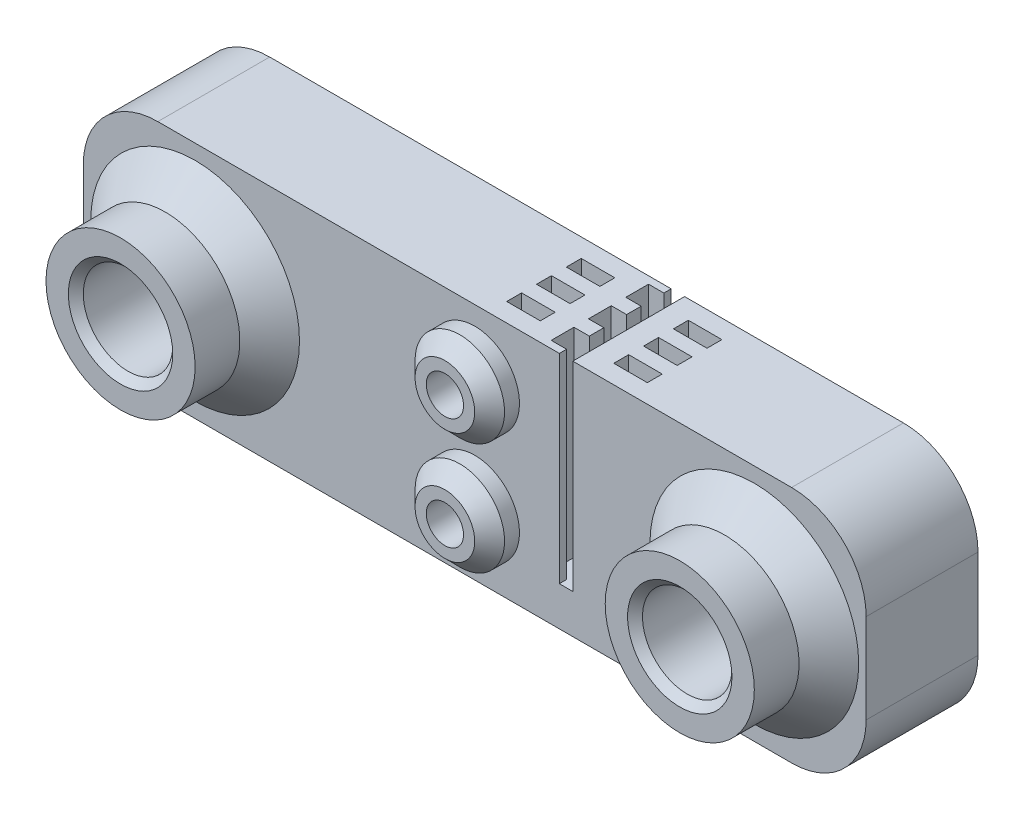
SolidWorks part; units mm, degrees
material "PEI"
ref_plane "前视基准面" through (0, 0, 0) normal (0, 0, 1) x (1, 0, 0)
ref_plane "上视基准面" through (0, 0, 0) normal (0, 1, 0) x (1, 0, 0)
ref_plane "右视基准面" through (0, 0, 0) normal (1, 0, 0) x (0, 0, -1)
sketch "草图1" plane through (0, 0, 0) normal (0, 0, 1) x (1, 0, 0)
  line L1 (-42.5, 16) -> (42.5, 16)
  line L2 (-52.5, 6) -> (-52.5, -6)
  line L3 (-42.5, -16) -> (42.5, -16)
  line L4 (52.5, 6) -> (52.5, -6)
  line L5 (-52.5, 16) -> (52.5, -16) construction
  line L6 (-52.5, -16) -> (52.5, 16) construction
  circle A0 centre (-37.5, 0) radius 6
  circle A1 centre (37.5, 0) radius 6
  arc A2 (-52.5, 6) -> (-42.5, 16) centre (-42.5, 6) cw
  arc A3 (-42.5, -16) -> (-52.5, -6) centre (-42.5, -6) cw
  arc A4 (52.5, 6) -> (42.5, 16) centre (42.5, 6) ccw
  arc A5 (42.5, -16) -> (52.5, -6) centre (42.5, -6) ccw
  point P0 (0, 0)
  dimension "D3" = 12
  dimension "D4" = 12
  dimension "D6" = 0
  dimension "D9" = 10
  dimension "D10" = 10
  dimension "D11" = 10
  dimension "D12" = 10
  dimension "D1" = 105
  dimension "D2" = 32
  dimension "D5" = 0
  dimension "D7" = 37.5
  dimension "D8" = 37.5
extrude "凸台-拉伸1" add sketch "草图1" along normal mid plane 15
sketch "草图2" plane through (0, 16, 0) normal (0, 1, 0) x (1, 0, 0)
  line L0 (42.5, 7.5) -> (-42.5, 7.5) construction
  line L1 (42.5, -7.5) -> (-42.5, -7.5) construction
  line L2 (13.15, 7.5) -> (11.35, 7.5)
  line L3 (13.15, 7.5) -> (13.15, -7.5)
  line L4 (13.15, -7.5) -> (11.35, -7.5)
  line L5 (11.35, 7.5) -> (11.35, 6.52)
  line L7 (11.35, 3.47) -> (11.35, 1.52)
  line L8 (9.29, 6.52) -> (11.35, 6.52)
  line L9 (9.29, 6.52) -> (9.29, 3.47)
  line L10 (9.29, 3.47) -> (11.35, 3.47)
  line L12 (9.29, 1.52) -> (11.35, 1.52)
  line L13 (9.29, 1.52) -> (9.29, -1.53)
  line L14 (9.29, -1.53) -> (11.35, -1.53)
  line L16 (9.29, -3.48) -> (11.35, -3.48)
  line L17 (9.29, -3.48) -> (9.29, -6.53)
  line L18 (9.29, -6.53) -> (11.35, -6.53)
  line L20 (11.35, -1.53) -> (11.35, -3.48)
  line L21 (11.35, -6.53) -> (11.35, -7.5)
  point P17 (10.32, 3.47)
  dimension "D1" = 11.35
  dimension "D2" = 1.8
  dimension "D3" = 0.98
  dimension "D4" = 3.05
  dimension "D5" = 2.06
  dimension "D6" = 1.95
  dimension "D7" = 3.05
  dimension "D8" = 2.06
  dimension "D10" = 3.05
  dimension "D11" = 2.06
  dimension "D12" = 1.95
extrude "切除-拉伸1" cut sketch "草图2" against normal blind 26.75 contours L20 L16 L17 L18 L21 L4 L3 L2 L5 L8 L9 L10 L7 L12 L13 L14
sketch "草图4" plane through (0, 16, 0) normal (0, 1, 0) x (1, 0, 0)
  line L0 (11.35, 7.5) -> (-42.5, 7.5) construction
  line L1 (1.79, 5) -> (6.29, 5)
  line L2 (1.79, 5) -> (1.79, 3)
  line L3 (1.79, 3) -> (6.29, 3)
  line L4 (6.29, 5) -> (6.29, 3)
  line L5 (1.79, 1) -> (6.29, 1)
  line L6 (1.79, 1) -> (1.79, -1)
  line L7 (1.79, -1) -> (6.29, -1)
  line L8 (6.29, 1) -> (6.29, -1)
  line L9 (1.79, -3) -> (6.29, -3)
  line L10 (1.79, -3) -> (1.79, -5)
  line L11 (1.79, -5) -> (6.29, -5)
  line L12 (6.29, -3) -> (6.29, -5)
  line L13 (16.15, 5) -> (20.65, 5)
  line L14 (16.15, 5) -> (16.15, 3)
  line L15 (16.15, 3) -> (20.65, 3)
  line L16 (20.65, 5) -> (20.65, 3)
  line L17 (16.15, 1) -> (20.65, 1)
  line L18 (16.15, 1) -> (16.15, -1)
  line L19 (16.15, -1) -> (20.65, -1)
  line L20 (20.65, 1) -> (20.65, -1)
  line L21 (16.15, -3) -> (20.65, -3)
  line L22 (16.15, -3) -> (16.15, -5)
  line L23 (16.15, -5) -> (20.65, -5)
  line L24 (20.65, -3) -> (20.65, -5)
  line L26 (42.5, 7.5) -> (13.15, 7.5) construction
  line L27 (9.29, 6.52) -> (9.29, 3.47) construction
  line L28 (13.15, 7.5) -> (13.15, -7.5) construction
  dimension "D1" = 2
  dimension "D2" = 2
  dimension "D3" = 2
  dimension "D4" = 4.5
  dimension "D5" = 4.5
  dimension "D6" = 4.5
  dimension "D7" = 4.5
  dimension "D8" = 4.5
  dimension "D9" = 4.5
  dimension "D10" = 2
  dimension "D11" = 2
  dimension "D12" = 2
  dimension "D13" = 2.5
  dimension "D14" = 2
  dimension "D15" = 2
  dimension "D16" = 2.5
  dimension "D17" = 2
  dimension "D18" = 2
  dimension "D19" = 3
  dimension "D20" = 3
extrude "切除-拉伸2" cut sketch "草图4" against normal blind 7
sketch "草图5" plane through (0, 0, 7.5) normal (0, 0, 1) x (1, 0, 0)
  circle A0 centre (-37.5, 0) radius 6
  circle A1 centre (-37.5, 0) radius 10
  circle A2 centre (37.5, 0) radius 6
  circle A3 centre (37.5, 0) radius 10
  dimension "D1" = 12
  dimension "D2" = 20
  dimension "D3" = 12
  dimension "D4" = 20
extrude "凸台-拉伸2" add sketch "草图5" along normal blind 10
chamfer "倒角1" distance 4 angle 45 2 edges at (27.5, 0, 7.5) (-47.5, 0, 7.5)
chamfer "倒角2" distance 1 angle 45 2 edges at (43.5, 0, 17.5) (-31.5, 0, 17.5)
sketch "草图6" plane through (0, 0, -7.5) normal (0, 0, -1) x (-1, 0, 0)
  line L0 (-52.5, -6) -> (-52.5, 6) construction
  line L1 (-11.35, 16) -> (42.5, 16) construction
  line L2 (52.5, 6) -> (52.5, -6) construction
  circle A0 centre (0, 7.5) radius 1.5
  circle A1 centre (0, -7.5) radius 1.5
  point P6 (7.5247, -3.1402)
  point P7 (5.4427, 2.7587)
  point P8 (-52.5, 4.9274)
  dimension "D1" = 3
  dimension "D2" = 3
  dimension "D4" = 52.5
  dimension "D6" = 52.5
  dimension "D3" = 15
  dimension "D5" = 8.5
extrude "切除-拉伸3" cut sketch "草图6" against normal through all contours A0 | A1
sketch "草图8" plane through (0, 0, 7.5) normal (0, 0, 1) x (1, 0, 0)
  circle A0 centre (0, 7.5) radius 2.5
  circle A1 centre (0, -7.5) radius 2.5
  dimension "D1" = 5
  dimension "D2" = 5
extrude "切除-拉伸4" cut sketch "草图8" against normal offset from surface (8 mm away) 7 up to face at (-1.5, 7.5, -7.5)
sketch "草图9" plane through (0, 0, 7.5) normal (0, 0, 1) x (1, 0, 0)
  circle A0 centre (0, 7.5) radius 6
  circle A1 centre (0, -7.5) radius 6
  circle A2 centre (0, 7.5) radius 2.5
  circle A3 centre (0, -7.5) radius 2.5
  dimension "D1" = 12
  dimension "D2" = 12
extrude "凸台-拉伸3" add sketch "草图9" along normal blind 4
chamfer "倒角4" distance 2 angle 45 2 edges at (6, -7.5, 11.5) (6, 7.5, 11.5)
